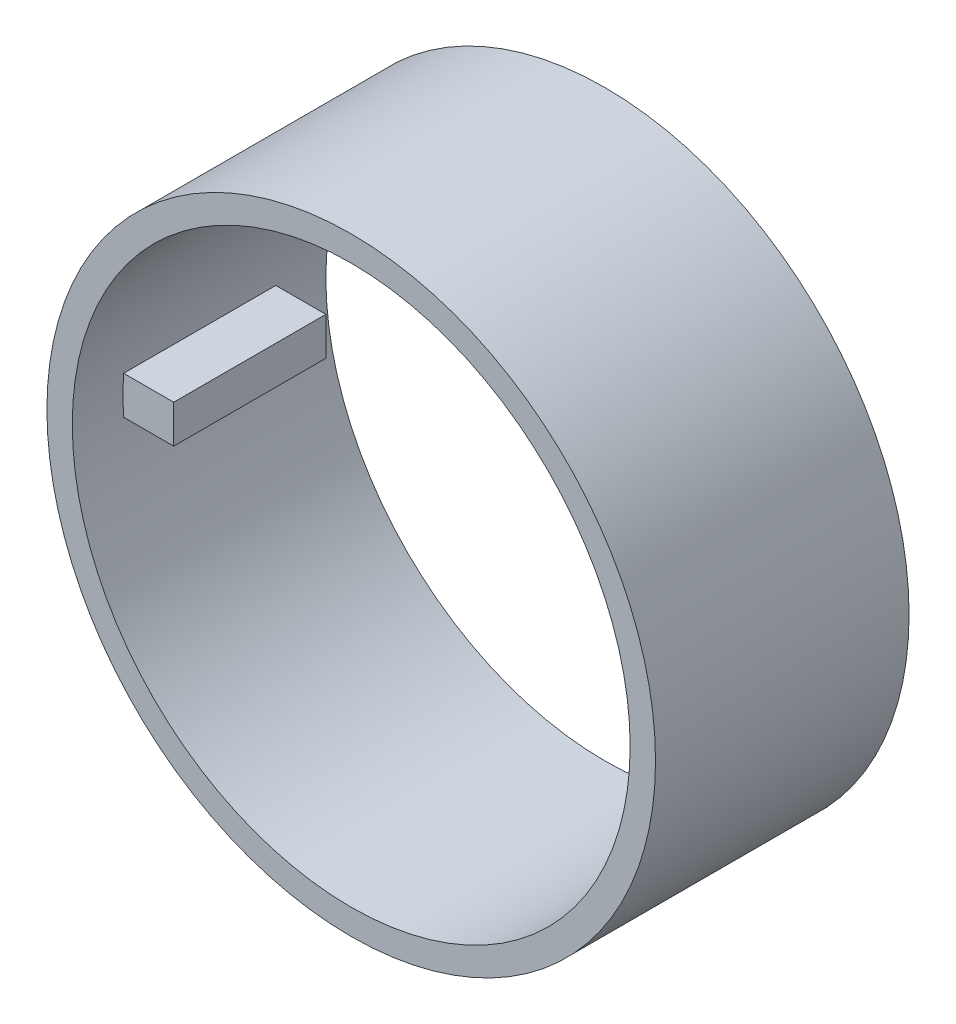
SolidWorks part; units mm, degrees
material "6061 Alloy"
ref_plane "Front Plane" through (0, 0, 0) normal (0, 0, 1) x (1, 0, 0)
ref_plane "Top Plane" through (0, 0, 0) normal (0, 1, 0) x (1, 0, 0)
ref_plane "Right Plane" through (0, 0, 0) normal (1, 0, 0) x (0, 0, -1)
sketch "Sketch1" plane through (0, 0, 0) normal (0, 0, 1) x (1, 0, 0)
  circle A0 centre (0, 0) radius 152.4
  circle A1 centre (0, 0) radius 139.7
  dimension "D1" = 304.8
  dimension "D2" = 279.4
extrude "Boss-Extrude1" add sketch "Sketch1" along normal mid plane 127
sketch "Sketch2" plane through (0, 0, 0) normal (0, 0, 1) x (1, 0, 0)
  line L1 (-149.225, 9.525) -> (-114.3, 9.525)
  line L2 (-149.225, 9.525) -> (-149.225, -9.525)
  line L3 (-149.225, -9.525) -> (-114.3, -9.525)
  line L4 (-114.3, 9.525) -> (-114.3, -9.525)
  circle A0 centre (0, 0) radius 139.7 construction
  dimension "D1" = 114.3
  dimension "D2" = 149.225
  dimension "D3" = 19.05
  dimension "D4" = 9.525
extrude "Boss-Extrude2" add sketch "Sketch2" along normal mid plane 76.2
mirror "Mirror2" about plane through (0, 0, 0) normal (1, 0, 0) of "Boss-Extrude2"
